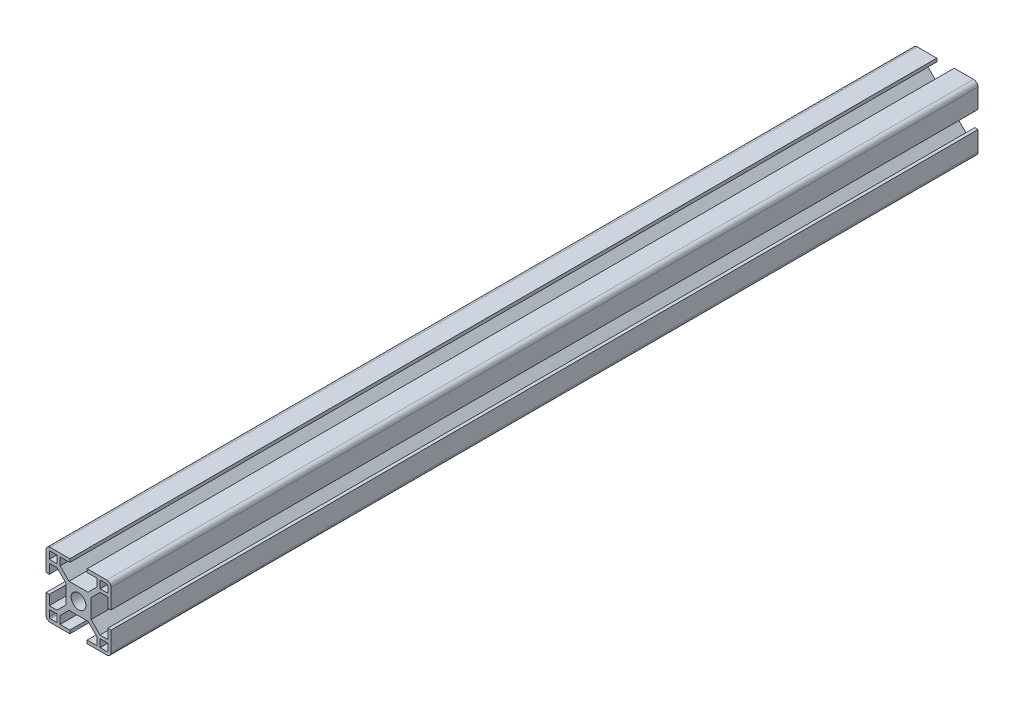
SolidWorks part; units mm, degrees
material "Stop 1060"
ref_plane "Płaszczyzna przednia" through (0, 0, 0) normal (0, 0, 1) x (1, 0, 0)
ref_plane "Płaszczyzna górna" through (0, 0, 0) normal (0, 1, 0) x (1, 0, 0)
ref_plane "Płaszczyzna prawa" through (0, 0, 0) normal (1, 0, 0) x (0, 0, -1)
sketch "Szkic1" plane through (0, 0, 0) normal (0, 0, 1) x (1, 0, 0)
  line L0 (0, 16.8101) -> (0, 0) construction
  line L1 (0, 0) -> (16.8101, 0) construction
  line L2 (0, 5.8) -> (4.3858, 5.8)
  line L3 (5.8, 4.3858) -> (5.8, 0)
  line L4 (10, 13.5) -> (13, 13.5)
  line L6 (4, 15) -> (4, 13.5)
  line L7 (4, 13.5) -> (8.5, 13.5)
  line L9 (13, 15) -> (4, 15)
  line L11 (15, 4) -> (13.5, 4)
  line L12 (13.5, 13) -> (13.5, 10)
  line L15 (9.9142, 8.5) -> (13.5, 8.5)
  line L16 (10, 13.5) -> (10, 10)
  line L18 (8.5, 9.9142) -> (8.5, 13.5)
  line L19 (10, 10) -> (13.5, 10)
  line L20 (15, 4) -> (15, 13)
  line L21 (13.5, 8.5) -> (13.5, 4)
  line L22 (0, 0) -> (22.7486, 22.7486) construction
  line L23 (5.8, 4.3858) -> (9.9142, 8.5)
  line L24 (4.3858, 5.8) -> (8.5, 9.9142)
  line L25 (4.3858, -5.8) -> (0, -5.8)
  line L26 (5.8, 0) -> (5.8, -4.3858)
  line L27 (5.8, -4.3858) -> (9.9142, -8.5)
  line L28 (4.3858, -5.8) -> (8.5, -9.9142)
  line L29 (8.5, -9.9142) -> (8.5, -13.5)
  line L30 (10, -10) -> (10, -13.5)
  line L31 (13.5, -10) -> (10, -10)
  line L32 (9.9142, -8.5) -> (13.5, -8.5)
  line L33 (13.5, -4) -> (13.5, -8.5)
  line L34 (15, -4) -> (13.5, -4)
  line L35 (15, -13) -> (15, -4)
  line L36 (13.5, -10) -> (13.5, -13)
  line L37 (13, -13.5) -> (10, -13.5)
  line L38 (8.5, -13.5) -> (4, -13.5)
  line L39 (4, -15) -> (13, -15)
  line L40 (4, -15) -> (4, -13.5)
  line L41 (-5.8, -4.3858) -> (-5.8, 0)
  line L42 (0, -5.8) -> (-4.3858, -5.8)
  line L43 (-4.3858, -5.8) -> (-8.5, -9.9142)
  line L44 (-5.8, -4.3858) -> (-9.9142, -8.5)
  line L45 (-9.9142, -8.5) -> (-13.5, -8.5)
  line L46 (-10, -10) -> (-13.5, -10)
  line L47 (-10, -13.5) -> (-10, -10)
  line L48 (-8.5, -9.9142) -> (-8.5, -13.5)
  line L49 (-4, -13.5) -> (-8.5, -13.5)
  line L50 (-4, -15) -> (-4, -13.5)
  line L51 (-13, -15) -> (-4, -15)
  line L52 (-10, -13.5) -> (-13, -13.5)
  line L53 (-13.5, -13) -> (-13.5, -10)
  line L54 (-13.5, -8.5) -> (-13.5, -4)
  line L55 (-15, -4) -> (-15, -13)
  line L56 (-15, -4) -> (-13.5, -4)
  line L57 (-4.3858, 5.8) -> (0, 5.8)
  line L58 (-5.8, 0) -> (-5.8, 4.3858)
  line L59 (-5.8, 4.3858) -> (-9.9142, 8.5)
  line L60 (-4.3858, 5.8) -> (-8.5, 9.9142)
  line L61 (-8.5, 9.9142) -> (-8.5, 13.5)
  line L62 (-10, 10) -> (-10, 13.5)
  line L63 (-13.5, 10) -> (-10, 10)
  line L64 (-9.9142, 8.5) -> (-13.5, 8.5)
  line L65 (-13.5, 4) -> (-13.5, 8.5)
  line L66 (-15, 4) -> (-13.5, 4)
  line L67 (-15, 13) -> (-15, 4)
  line L68 (-13.5, 10) -> (-13.5, 13)
  line L69 (-13, 13.5) -> (-10, 13.5)
  line L70 (-8.5, 13.5) -> (-4, 13.5)
  line L71 (-4, 15) -> (-13, 15)
  line L72 (-4, 15) -> (-4, 13.5)
  arc A0 (0, -3.4) -> (-3.4, 0) centre (0, 0) cw
  arc A1 (13, 13.5) -> (13.5, 13) centre (13, 13) cw
  arc A2 (15, 13) -> (13, 15) centre (13, 13) ccw
  arc A3 (-3.4, 0) -> (0, -3.4) centre (0, 0) cw
  arc A4 (0, 3.4) -> (3.4, 0) centre (0, 0) cw
  arc A5 (3.4, 0) -> (0, 3.4) centre (0, 0) cw
  arc A6 (13, -15) -> (15, -13) centre (13, -13) ccw
  arc A7 (13.5, -13) -> (13, -13.5) centre (13, -13) cw
  arc A8 (-15, -13) -> (-13, -15) centre (-13, -13) ccw
  arc A9 (-13, -13.5) -> (-13.5, -13) centre (-13, -13) cw
  arc A10 (-13, 15) -> (-15, 13) centre (-13, 13) ccw
  arc A11 (-13.5, 13) -> (-13, 13.5) centre (-13, 13) cw
  point P8 (2.1929, 5.8)
  point P37 (0, 0)
  point P100 (0, 0)
  dimension "D1" = 3.4
  dimension "D7" = 0.5
  dimension "D8" = 2
  dimension "D3" = 3.5
  dimension "D4" = 1.5
  dimension "D5" = 1.5
  dimension "D6" = 11
  dimension "D9" = 9.2
  dimension "D10" = 2
  dimension "D2" = 5.8
  dimension "D11" = 5.8
  dimension "D13" = 4
extrude "Dodanie-wyciągnięcie1" add sketch "Szkic1" along normal blind 400 contours L71 A10 L67 L66 L65 L64 L59 L58 L41 L44 L45 L54 L56 L55 A8 L51 L50 L49 L48 L43 L42 L25 L28 L29 L38 L40 L39 A6 L35 L34 L33 L32 L27 L26 L3 L23 L15 L21 L11 L20 A2 L9 L6 L7 L18 L24 L2 L57 L60 L61 L70 | A3 A0
sketch "Szkic2" plane through (0, 0, 0) normal (0, 0, 1) x (1, 0, 0)
  line L14 (-7, -13.5) -> (-3.5, -13.5)
  line L15 (3.5, -13.5) -> (7, -13.5)
  line L16 (13.5, -7) -> (13.5, -3.5)
  line L17 (13.5, 7) -> (13.5, 3.5)
  line L18 (-15.5, 3.5) -> (-15.5, 7.5)
  line L19 (13.5, 7.5) -> (10.3284, 7.5)
  line L20 (10.3284, 7.5) -> (6.8, 3.9716)
  line L21 (6.8, 3.9716) -> (6.8, -3.9716)
  line L22 (-13.5, -7.5) -> (-10.3284, -7.5)
  line L23 (-10.3284, 7.5) -> (-13.5, 7.5)
  line L24 (-6.8, 3.9716) -> (-10.3284, 7.5)
  line L25 (-10.3284, -7.5) -> (-6.8, -3.9716)
  line L26 (-6.8, -3.9716) -> (-6.8, 3.9716)
  line L27 (-13, -7.5) -> (-11.5711, -7.5)
  line L28 (-11.5711, 7.5) -> (-13, 7.5)
  line L29 (-7.6787, 4.8503) -> (-9.4497, 6.6213)
  line L30 (-9.4497, -6.6213) -> (-7.6787, -4.8503)
  line L31 (-6.8, -2.7289) -> (-6.8, 2.7289)
  line L32 (6.8, -3.9716) -> (10.3284, -7.5)
  line L33 (10.3284, -7.5) -> (13.5, -7.5)
  line L34 (-15, -3.5) -> (-13.5, -3.5)
  line L35 (-15.5, -3.5) -> (-13.5, -3.5)
  line L36 (-13.5, 3.5) -> (-13.5, 7)
  line L37 (-15, 3.5) -> (-13.5, 3.5)
  line L38 (-15.5, 3.5) -> (-13.5, 3.5)
  line L39 (-13.5, -3.5) -> (-13.5, -7)
  line L40 (13, 7.5) -> (11.5711, 7.5)
  line L41 (9.4497, 6.6213) -> (7.6787, 4.8503)
  line L42 (-3.5, -15) -> (-3.5, -13.5)
  line L43 (-3.5, -15.5) -> (-3.5, -13.5)
  line L44 (6.8, 2.7289) -> (6.8, -2.7289)
  line L45 (3.5, -15) -> (3.5, -13.5)
  line L46 (3.5, -15.5) -> (3.5, -13.5)
  line L47 (7.6787, -4.8503) -> (9.4497, -6.6213)
  line L48 (15, -3.5) -> (13.5, -3.5)
  line L49 (15.5, -3.5) -> (13.5, -3.5)
  line L50 (11.5711, -7.5) -> (13, -7.5)
  line L51 (15, 3.5) -> (13.5, 3.5)
  line L52 (15.5, 3.5) -> (13.5, 3.5)
  line L53 (-15.5, 7.5) -> (-17.5, 7.5)
  line L55 (-20.5, -20.5) -> (20.5, -20.5)
  line L56 (20.5, -20.5) -> (20.5, 4.5)
  line L57 (17.5, 7.5) -> (15.5, 7.5)
  line L59 (15.5, 7.5) -> (15.5, 3.5)
  line L60 (-3.5, -15.5) -> (-13.5, -15.5)
  line L61 (-15.5, -13.5) -> (-15.5, -3.5)
  line L63 (3.5, -15.5) -> (13.5, -15.5)
  line L64 (15.5, -13.5) -> (15.5, -3.5)
  line L65 (-20.5, -20.5) -> (-20.5, 4.5)
  line L80 (7.5, -10.3284) -> (3.9716, -6.8)
  line L81 (7.5, -13.5) -> (7.5, -10.3284)
  line L82 (3.9716, -6.8) -> (-3.9716, -6.8)
  line L83 (-3.9716, -6.8) -> (-7.5, -10.3284)
  line L84 (-7.5, -10.3284) -> (-7.5, -13.5)
  line L85 (6.6213, -9.4497) -> (4.8503, -7.6787)
  line L86 (7.5, -13) -> (7.5, -11.5711)
  line L87 (2.7289, -6.8) -> (-2.7289, -6.8)
  line L88 (-4.8503, -7.6787) -> (-6.6213, -9.4497)
  line L89 (-7.5, -11.5711) -> (-7.5, -13)
  arc A0 (20.5, 4.5) -> (17.5, 7.5) centre (17.5, 4.5) ccw
  arc A1 (-6.6213, -9.4497) -> (-7.5, -11.5711) centre (-4.5, -11.5711) ccw
  arc A2 (-2.7289, -6.8) -> (-4.8503, -7.6787) centre (-2.7289, -9.8) ccw
  arc A3 (4.8503, -7.6787) -> (2.7289, -6.8) centre (2.7289, -9.8) ccw
  arc A4 (6.6213, -9.4497) -> (7.5, -11.5711) centre (4.5, -11.5711) cw
  arc A5 (9.4497, -6.6213) -> (11.5711, -7.5) centre (11.5711, -4.5) ccw
  arc A6 (6.8, -2.7289) -> (7.6787, -4.8503) centre (9.8, -2.7289) ccw
  arc A7 (7.6787, 4.8503) -> (6.8, 2.7289) centre (9.8, 2.7289) ccw
  arc A8 (11.5711, 7.5) -> (9.4497, 6.6213) centre (11.5711, 4.5) ccw
  arc A9 (-11.5711, -7.5) -> (-9.4497, -6.6213) centre (-11.5711, -4.5) ccw
  arc A10 (-7.6787, -4.8503) -> (-6.8, -2.7289) centre (-9.8, -2.7289) ccw
  arc A11 (-7.6787, 4.8503) -> (-6.8, 2.7289) centre (-9.8, 2.7289) cw
  arc A12 (-11.5711, 7.5) -> (-9.4497, 6.6213) centre (-11.5711, 4.5) cw
  arc A13 (-17.5, 7.5) -> (-20.5, 4.5) centre (-17.5, 4.5) ccw
  arc A14 (13, 7.5) -> (13.5, 7) centre (13, 7) cw
  arc A15 (13, -7.5) -> (13.5, -7) centre (13, -7) ccw
  arc A16 (7.5, -13) -> (7, -13.5) centre (7, -13) cw
  arc A17 (-7.5, -13) -> (-7, -13.5) centre (-7, -13) ccw
  arc A18 (-13, -7.5) -> (-13.5, -7) centre (-13, -7) cw
  arc A19 (-13, 7.5) -> (-13.5, 7) centre (-13, 7) ccw
  arc A20 (13.5, -15.5) -> (15.5, -13.5) centre (13.5, -13.5) ccw
  arc A21 (-13.5, -15.5) -> (-15.5, -13.5) centre (-13.5, -13.5) cw
  point P34 (20.5, 7.5)
  dimension "D7" = 0.5
  dimension "D10" = 2
  dimension "D13" = 3
  dimension "D14" = 3
  dimension "D16" = 3
  dimension "D17" = 0.5
  dimension "D18" = 2
  dimension "D11" = 5
  dimension "D12" = 5
  dimension "D15" = 5
  dimension "D1" = 1
  dimension "D2" = 0.5
  dimension "D3" = 0.5
  dimension "D4" = 0.5
  dimension "D5" = 0.5
  dimension "D6" = 0.5
  dimension "D8" = 1
  dimension "D9" = 1
equation "\"D5@Szkic1\"=\"D4@Szkic1\""
equation "\"D15@Szkic2\"=\"D11@Szkic2\""
